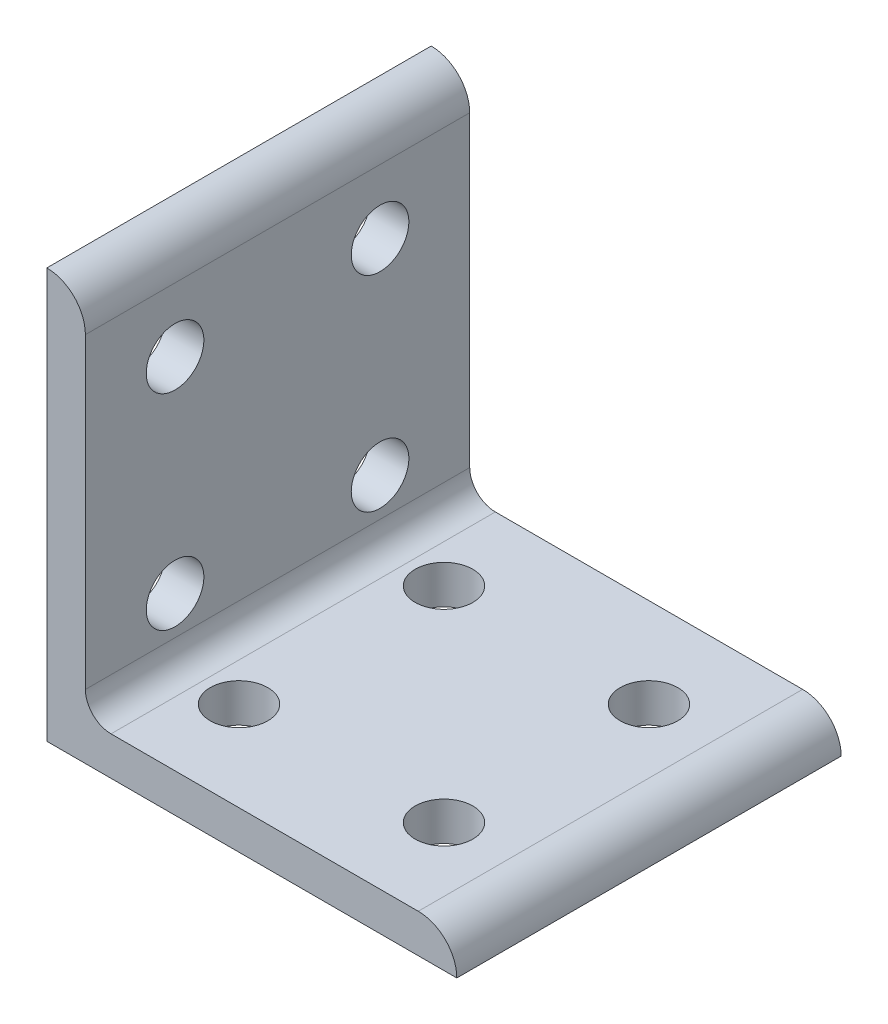
SolidWorks part; units mm, degrees
ref_plane "Front Plane" through (0, 0, 0) normal (0, 0, 1) x (1, 0, 0)
ref_plane "Top Plane" through (0, 0, 0) normal (0, 1, 0) x (1, 0, 0)
ref_plane "Right Plane" through (0, 0, 0) normal (1, 0, 0) x (0, 0, -1)
sketch "Sketch1" plane through (0, 0, 0) normal (0, 0, 1) x (1, 0, 0)
  line L0 (0, 0) -> (0, 50.8)
  line L1 (4.7752, 46.0248) -> (4.7752, 50.8) construction
  line L2 (4.7752, 46.0248) -> (4.7752, 7.9502)
  line L3 (7.9502, 4.7752) -> (46.0248, 4.7752)
  line L4 (4.7752, 50.8) -> (0, 50.8) construction
  line L5 (50.8, 0) -> (0, 0)
  line L6 (46.0248, 4.7752) -> (50.8, 4.7752) construction
  line L7 (50.8, 4.7752) -> (50.8, 0) construction
  arc A0 (4.7752, 46.0248) -> (0, 50.8) centre (0, 46.0248) ccw
  arc A1 (50.8, 0) -> (46.0248, 4.7752) centre (46.0248, 0) ccw
  arc A2 (4.7752, 7.9502) -> (7.9502, 4.7752) centre (7.9502, 7.9502) ccw
  point P10 (4.7752, 48.4124)
  dimension "E" = 3.175
  dimension "D" = 4.7752
  dimension "C" = 50.8
  dimension "B" = 50.8
extrude "Boss-Extrude1" add sketch "Sketch1" along normal mid plane 47.625
sketch "Sketch2" plane through (0, 0, 0) normal (0, 1, 0) x (1, 0, 0)
  line L0 (0, -12.7) -> (12.7, -12.7) construction
  line L1 (12.7, -12.7) -> (38.1, -12.7) construction
  line L2 (0, -12.7) -> (0, 12.7) construction
  line L3 (0, 12.7) -> (12.7, 12.7) construction
  line L4 (38.1, 12.7) -> (38.1, -12.7) construction
  line L5 (0, -12.7) -> (0, -23.8125) construction
  line L6 (12.7, -12.7) -> (12.7, 12.7) construction
  line L7 (12.7, 12.7) -> (38.1, 12.7) construction
  circle A0 centre (12.7, -12.7) radius 3.5687
  circle A1 centre (38.1, -12.7) radius 3.5687
  circle A2 centre (12.7, 12.7) radius 3.5687
  circle A3 centre (38.1, 12.7) radius 3.5687
extrude "Cut-Extrude1" cut sketch "Sketch2" along normal through all
sketch "Sketch3" plane through (0, 0, 0) normal (1, 0, 0) x (0, 0, -1)
  line L0 (-12.7, 0) -> (-12.7, 12.7) construction
  line L1 (-12.7, 12.7) -> (-12.7, 38.1) construction
  line L2 (12.7, 0) -> (12.7, 12.7) construction
  line L3 (12.7, 12.7) -> (-12.7, 12.7) construction
  line L4 (12.7, 12.7) -> (12.7, 38.1) construction
  line L5 (12.7, 38.1) -> (-12.7, 38.1) construction
  circle A0 centre (-12.7, 12.7) radius 3.5687
  circle A1 centre (-12.7, 38.1) radius 3.5687
  circle A2 centre (12.7, 12.7) radius 3.5687
  circle A3 centre (12.7, 38.1) radius 3.5687
  dimension "D1" = 12.7
  dimension "D2" = 25.4
extrude "Cut-Extrude2" cut sketch "Sketch3" along normal through all
equation "\"E@Sketch3\" = \"E@Sketch2\""
equation "\"D1@Sketch3\" = \"D1@Sketch2\""
equation "\"D2@Sketch3\" = \"D2@Sketch2\""
